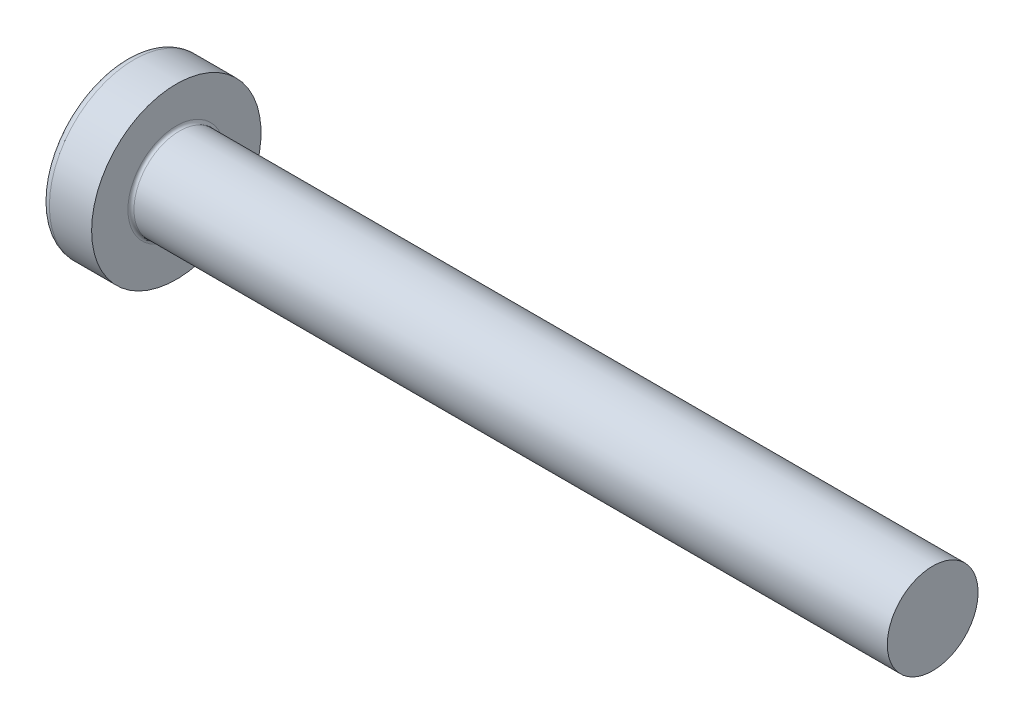
SolidWorks part; units mm, degrees
ref_plane "Plane1" through (0, 0, 0) normal (0, 0, 1) x (1, 0, 0)
ref_plane "Plane2" through (0, 0, 0) normal (0, 1, 0) x (1, 0, 0)
ref_plane "Plane3" through (0, 0, 0) normal (1, 0, 0) x (0, 0, -1)
sketch "BodySke" plane through (0, 0, 0) normal (0, 0, 1) x (1, 0, 0)
  line L0 (2.4, 1.5) -> (2.4, 2.8)
  line L1 (2.65, 6.35) -> (2.65, -3.175) construction
  line L2 (-25.4, 0) -> (127, 0) construction
  line L3 (27.4, 0) -> (0, 0)
  line L4 (2.4, 1.5) -> (27.4, 1.5)
  line L5 (27.4, 1.5) -> (27.4, 0)
  line L6 (1.0035, 2.8) -> (2.4, 2.8)
  line L8 (2.4, 6.35) -> (2.4, -3.175) construction
  arc A0 (0.7754, 2.6744) -> (0, 0) centre (5, 0) ccw
  arc A2 (0.7754, 2.6744) -> (1.0035, 2.8) centre (1.0035, 2.53) cw
  dimension "Head_crown_rad" = 5
  dimension "Head_fillet_rad" = 0.27
  dimension "Length" = 25
  dimension "Head_ht" = 2.4
  dimension "Head_dia" = 5.6
  dimension "Advance" = 0.5
  dimension "Thread_nom" = 25
  dimension "Diameter" = 3
revolve "Base-Revolve" add sketch "BodySke"
cosmetic thread "ThreadCosmetic" [suppressed]
fillet "Fillet1" radius 0.1 1 edges at (2.4, 0, 1.5)
sketch "Sketch3" plane through (0, 0, 0) normal (1, 0, 0) x (0, 0, -1)
  line L0 (0.37, -1.4) -> (-0.37, -1.4)
  line L1 (0.37, -1.4) -> (0.37, 1.4)
  line L2 (-0.37, 1.4) -> (0.37, 1.4)
  line L3 (-0.37, 1.4) -> (-0.37, -1.4)
  dimension "Cross_dia" = 2.8
  dimension "D1" = 1.4
  dimension "Cross_width" = 0.74
  dimension "D2" = 0.37
ref_plane "Plane4" through (1.75, 0, 0) normal (1, 0, 0) x (0, 0, -1)
sketch "Sketch4" plane through (1.75, 0, 0) normal (1, 0, 0) x (0, 0, -1)
  line L0 (0.37, -0.5275) -> (-0.37, -0.5275)
  line L1 (0.37, -0.5275) -> (0.37, 0.5275)
  line L2 (-0.37, 0.5275) -> (0.37, 0.5275)
  line L3 (-0.37, 0.5275) -> (-0.37, -0.5275)
  dimension "D1" = 0.74
  dimension "D2" = 1.055
  dimension "D3" = 0.37
  dimension "D4" = 0.5275
loft "Recess" cut profiles "Sketch3", "Sketch4"
pattern_circular "RecPat" count 2 every 90 about axis through (0, 0, 0) along (1, 0, 0) of "Recess"
sketch "RecCorSke" plane through (0, 0, 0) normal (0, 0, 1) x (1, 0, 0)
  line L0 (-3.175, 0) -> (15.875, 0) construction
  line L1 (-25.4, 0) -> (127, 0) construction
  line L2 (0, 0) -> (0, 0.6784)
  line L3 (0, 0.6784) -> (1.75, 0.556)
  line L4 (1.75, 0.556) -> (1.9307, 0)
  line L5 (1.9307, 0) -> (0, 0)
  dimension "Diameter" = 1.112
  dimension "Depth" = 1.75
  dimension "Draft_angle" = 4
  dimension "Bottom_angle" = 18
revolve "RecessCore" cut sketch "RecCorSke" angle 360 about L0
sketch "ThdSchSke" plane through (0, 0, 0) normal (0, 0, 1) x (1, 0, 0)
  line L0 (3.4, -1.2195) -> (3.2036, -1.5)
  line L1 (3.4, -1.2195) -> (3.5964, -1.5)
  line L2 (3.5964, -1.5) -> (3.5964, -1.875)
  line L3 (-3.175, 0) -> (5.1513, 0) construction
  line L5 (3.5964, -1.875) -> (3.2036, -1.875)
  line L6 (3.2036, -1.875) -> (3.2036, -1.5)
  dimension "Diameter" = 3
  dimension "SideAngle" = 55
  dimension "VeeAngle" = 70
  dimension "Thread_minor" = 2.439
  dimension "Overcut" = 3.75
  dimension "Start" = 3.4
revolve "ThreadSchematic" [suppressed] cut sketch "ThdSchSke" angle 360 about L3
pattern_linear "ThdSchPat" [suppressed]
equation "\"D1@Sketch3\" = \"Cross_dia@Sketch3\" / 2"
equation "\"D2@Sketch3\" = \"Cross_width@Sketch3\" / 2"
equation "\"Depth@RecCorSke\" = \"Cross_depth@Plane4\""
equation "\"D1@Sketch4\" = \"Cross_width@Sketch3\""
equation "\"D2@Sketch4\" = \"Cross_dia@Sketch3\" - 2.0 * \"Cross_depth@Plane4\" * tan(26.5  * 0.017453292)"
equation "\"D3@Sketch4\" = \"D1@Sketch4\" / 2"
equation "\"D4@Sketch4\" = \"D2@Sketch4\" / 2"
equation "\"Thread_length@ThreadCosmetic\" = ((sgn( (\"Length@BodySke\" - \"Advance@BodySke\" * 2.0 ) - \"Thread_nom@BodySke\" )-1)*( (\"Length@BodySke\" - \"Advance@BodySke\" * 2.0 ) - \"Thread_nom@BodySke\" ))/-2+ \"Thread_nom@BodySke\""
equation "\"Thread_minor@ThdSchSke\" = \"Thread_minor@ThreadCosmetic\""
equation "\"Diameter@ThdSchSke\" = \"Diameter@BodySke\""
equation "\"Overcut@ThdSchSke\" = \"Diameter@BodySke\" * 1.25"
equation "\"Start@ThdSchSke\" = \"Head_ht@BodySke\" + \"Length@BodySke\" - \"Thread_length@ThreadCosmetic\"  '---Non-countersunk---"
equation "\"Num_threads@ThdSchPat\" = int( \"Thread_length@ThreadCosmetic\" / \"Advance@BodySke\" + 0.999 )  + 1"
equation "\"Advance@ThdSchPat\" = \"Thread_length@ThreadCosmetic\" /  (\"Num_threads@ThdSchPat\" - 1) 'relax it"
